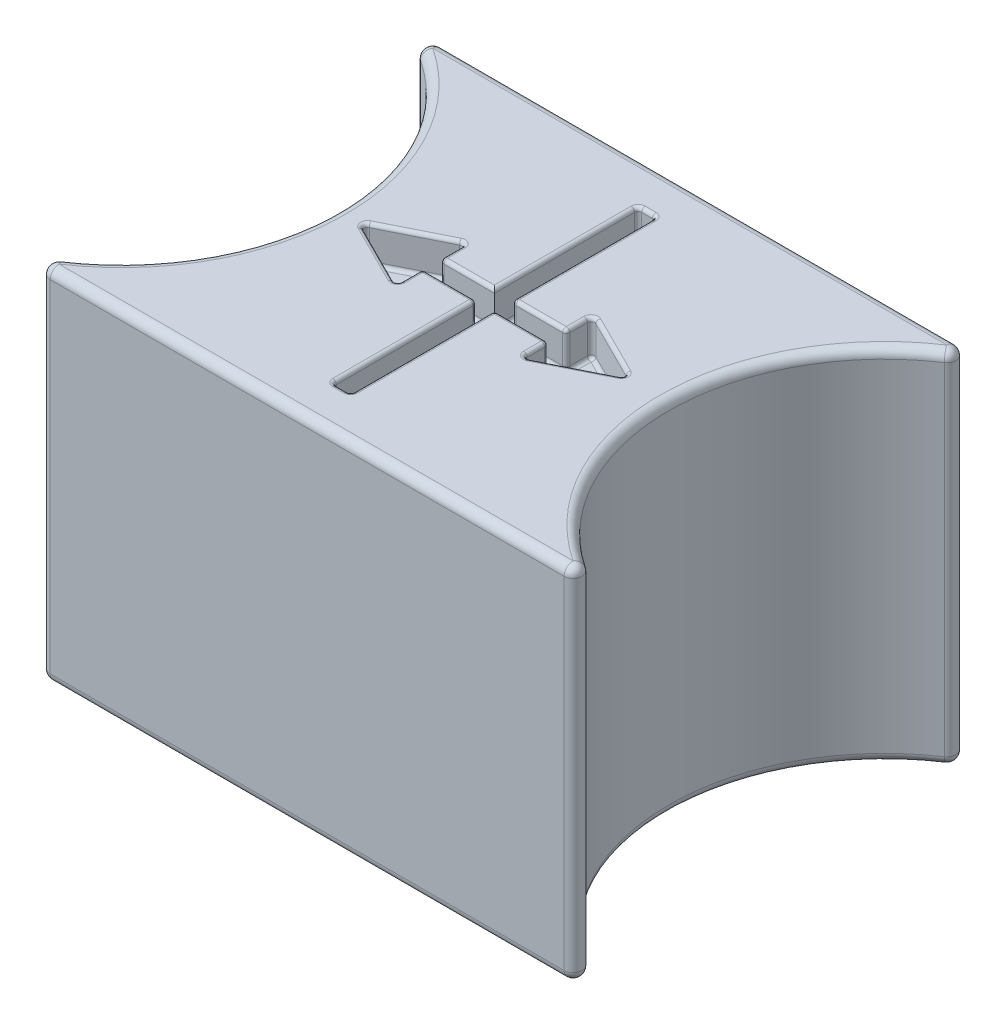
SolidWorks part; units mm, degrees
ref_plane "Front Plane" through (0, 0, 0) normal (0, 0, 1) x (1, 0, 0)
ref_plane "Top Plane" through (0, 0, 0) normal (0, 1, 0) x (1, 0, 0)
ref_plane "Right Plane" through (0, 0, 0) normal (1, 0, 0) x (0, 0, -1)
sketch "Sketch1" plane through (0, 0, 0) normal (0, 1, 0) x (1, 0, 0)
  line L1 (-16.2197, 0) -> (0, 0)
  line L2 (-16.2197, 0) -> (-16.2197, -10.9017)
  line L3 (-16.2197, -10.9017) -> (0, -10.9017)
  line L4 (0, 0) -> (0, -10.9017)
  dimension "D1" = 16.2197
  dimension "D2" = 10.9017
  dimension "D3" = 0
  dimension "D4" = 0
extrude "Boss-Extrude1" add sketch "Sketch1" along normal blind 10
sketch "Sketch2" plane through (0, 10, 0) normal (0, 1, 0) x (1, 0, 0)
  line L1 (-8.11, 3.763) -> (-8.11, -18.2775) construction
  circle A1 centre (-18.7273, -5.4509) radius 6
  circle A3 centre (2.5073, -5.4509) radius 6
  point P2 (-16.2197, 0)
  point P3 (-16.2197, -10.9017)
  point P14 (-0.0003, -10.9017)
  point P15 (-0.0003, 0)
  dimension "D1" = 6
  dimension "D3" = 8.11
  dimension "D2" = 6
extrude "Cut-Extrude1" cut sketch "Sketch2" against normal blind 10
fillet "Fillet1" radius 0.25 12 edges at (-8.11, 0, 0) (-8.11, 0, 10.9017) (-16.2197, 5, 10.9017) (-12.7273, 0, 5.4509) (-16.2197, 5, 0) (-12.7273, 10, 5.4509) (-8.11, 10, 0) (-8.11, 10, 10.9017) (-0.0003, 5, 0) (-3.4927, 0, 5.4509) (-0.0003, 5, 10.9017) (-3.4927, 10, 5.4509)
sketch "Sketch3" plane through (0, 0, 0) normal (0, -1, 0) x (1, 0, 0)
  circle A0 centre (-8.11, 5.45) radius 2.5
  dimension "D3" = 5
  dimension "D1" = 8.11
  dimension "D2" = 5.45
extrude "Cut-Extrude2" cut sketch "Sketch3" against normal blind 8
fillet "Fillet2" radius 2 1 edges at (-8.11, 8, 2.95)
sketch "Sketch4" plane through (0, 10, 0) normal (0, 1, 0) x (1, 0, 0)
  line L0 (-8.1, -5.7) -> (-6.6, -5.7)
  line L1 (-8.6, -1.2) -> (-8.1, -1.2)
  line L2 (-8.6, -1.2) -> (-8.6, -5.2)
  line L3 (-8.6, -9.7) -> (-8.1, -9.7)
  line L4 (-8.1, -1.2) -> (-8.1, -5.2)
  line L5 (-8.1, -5.2) -> (-6.6, -5.2)
  line L6 (-10.1, -4.45) -> (-10.1, -5.2)
  line L7 (-8.6, -5.2) -> (-10.1, -5.2)
  line L9 (-8.6, -5.7) -> (-10.1, -5.7)
  line L15 (-10.1, -6.45) -> (-12.1, -5.45)
  line L16 (-12.1, -5.45) -> (-10.1, -4.45)
  line L17 (-8.35, -0.4767) -> (-8.35, -10.3918) construction
  line L18 (-4.6, -5.45) -> (-6.6, -4.45)
  line L19 (-6.6, -6.45) -> (-4.6, -5.45)
  line L21 (-6.6, -4.45) -> (-6.6, -5.2)
  line L22 (-8.1, -5.7) -> (-8.1, -9.7)
  line L23 (-8.6, -5.7) -> (-8.6, -9.7)
  line L24 (-10.1, -5.7) -> (-10.1, -6.45)
  line L25 (-6.6, -5.7) -> (-6.6, -6.45)
  point P15 (-9.35, -5.7)
  point P18 (-7.35, -5.7)
  dimension "D1" = 0.5
  dimension "D2" = 8.1
  dimension "D3" = 8.5
  dimension "D4" = 1.2
  dimension "D5" = 0.5
  dimension "D8" = 4
  dimension "D9" = 1.5
  dimension "D11" = 2
  dimension "D12" = 0.75
  dimension "D13" = 2
  dimension "D14" = 1
extrude "Cut-Extrude3" cut sketch "Sketch4" against normal blind 1
fillet "Fillet3" radius 0.1 53 edges at (-6.6, 9.5, 4.45) (-9.35, 10, 5.2) (-11.1, 10, 5.95) (-8.6, 10, 7.7) (-8.1, 10, 7.7) (-5.6, 10, 4.95) (-6.6, 10, 4.825) (-8.1, 10, 3.2) (-8.6, 10, 3.2) (-8.1, 9.5, 1.2) (-8.6, 9.5, 1.2) (-8.35, 10, 1.2) (-8.6, 9.5, 9.7) (-8.1, 9.5, 9.7) (-8.35, 10, 9.7) (-8.6, 9.5, 5.7) (-9.35, 10, 5.7) (-8.1, 9.5, 5.7) (-7.35, 10, 5.7) (-4.6, 9.5, 5.45) (-5.6, 10, 5.95) (-6.6, 9.5, 5.7) (-6.6, 9.5, 6.45) (-6.6, 10, 6.075) (-6.6, 9.5, 5.2) (-8.1, 9.5, 5.2) (-7.35, 10, 5.2) (-12.1, 9.5, 5.45) (-11.1, 10, 4.95) (-10.1, 9.5, 5.2) (-10.1, 9.5, 4.45) (-10.1, 10, 4.825) (-10.1, 9.5, 6.45) (-10.1, 9.5, 5.7) (-10.1, 10, 6.075) (-8.35, 9, 1.2) (-8.1, 9, 3.2) (-7.35, 9, 5.2) (-6.6, 9, 4.825) (-5.6, 9, 4.95) (-5.6, 9, 5.95) (-6.6, 9, 6.075) (-7.35, 9, 5.7) (-8.1, 9, 7.7) (-8.35, 9, 9.7) (-8.6, 9, 7.7) (-9.35, 9, 5.7) (-10.1, 9, 6.075) (-11.1, 9, 5.95) (-11.1, 9, 4.95) (-10.1, 9, 4.825) (-9.35, 9, 5.2) (-8.6, 9, 3.2)
